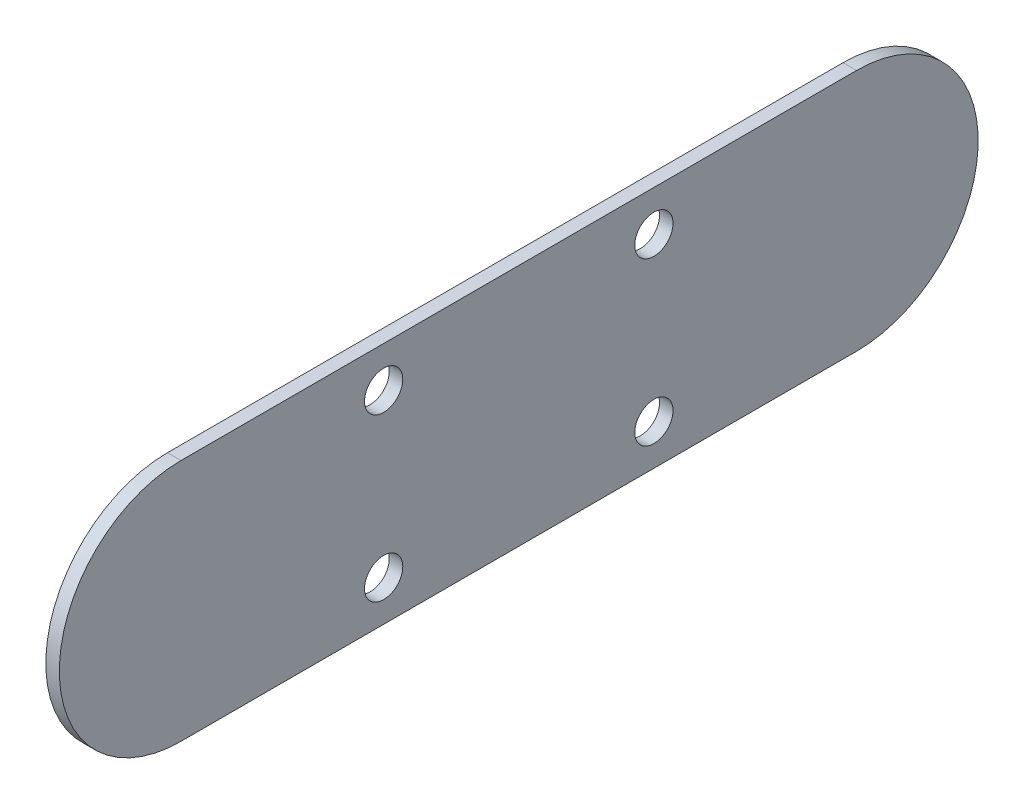
SolidWorks part; units mm, degrees
material "6061 Alloy"
ref_plane "Front Plane" through (0, 0, 0) normal (0, 0, 1) x (1, 0, 0)
ref_plane "Top Plane" through (0, 0, 0) normal (0, 1, 0) x (1, 0, 0)
ref_plane "Right Plane" through (0, 0, 0) normal (1, 0, 0) x (0, 0, -1)
sketch "Sketch2" plane through (0, 0, 0) normal (1, 0, 0) x (0, 0, -1)
  line L0 (39.6875, 0) -> (-39.6875, 0) construction
  line L1 (39.6875, -14.2875) -> (-39.6875, -14.2875)
  line L2 (39.6875, 14.2875) -> (-39.6875, 14.2875)
  arc A0 (39.6875, -14.2875) -> (39.6875, 14.2875) centre (39.6875, 0) ccw
  arc A1 (-39.6875, 14.2875) -> (-39.6875, -14.2875) centre (-39.6875, 0) ccw
  point P2 (0, 0)
  dimension "D2" = 28.575
  dimension "D1" = 79.375
extrude "Boss-Extrude1" add sketch "Sketch2" along normal blind 1.5875
sketch "Sketch3" plane through (1.5875, 0, 0) normal (1, 0, 0) x (0, 0, -1)
  line L1 (15.875, -9.525) -> (-15.875, -9.525)
  line L2 (15.875, -9.525) -> (15.875, 9.525)
  line L3 (15.875, 9.525) -> (-15.875, 9.525)
  line L4 (-15.875, -9.525) -> (-15.875, 9.525)
  line L5 (15.875, -9.525) -> (-15.875, 9.525) construction
  line L6 (15.875, 9.525) -> (-15.875, -9.525) construction
  point P0 (0, 0)
  dimension "D1" = 31.75
  dimension "D2" = 19.05
hole_wizard "#8 Clearance Hole1" positions "Sketch4" profile "Sketch5" hole size "#8" standard "ANSI Inch" end condition up to next
sketch "Sketch4" plane through (1.5875, 0, 0) normal (1, 0, 0) x (0, 0, -1)
  point P0 (-15.875, 9.525)
  point P3 (-15.875, -9.525)
  point P6 (15.875, -9.525)
  point P9 (15.875, 9.525)
sketch "Sketch5" plane through (1.5875, 9.525, 15.875) normal (0, 1, 0) x (0, 0, -1)
  line L0 (0, 0) -> (0, 1.5875)
  line L1 (0, 1.5875) -> (2.2479, 1.5875)
  line L2 (2.2479, 1.5875) -> (2.2479, 0)
  line L5 (2.2479, 0) -> (0, 0)
  line L11 (0, -6.35) -> (0, 107.95) construction
  dimension "Thru Hole Dia." = 4.4958
  dimension "Thru Hole Depth" = 1.5875
